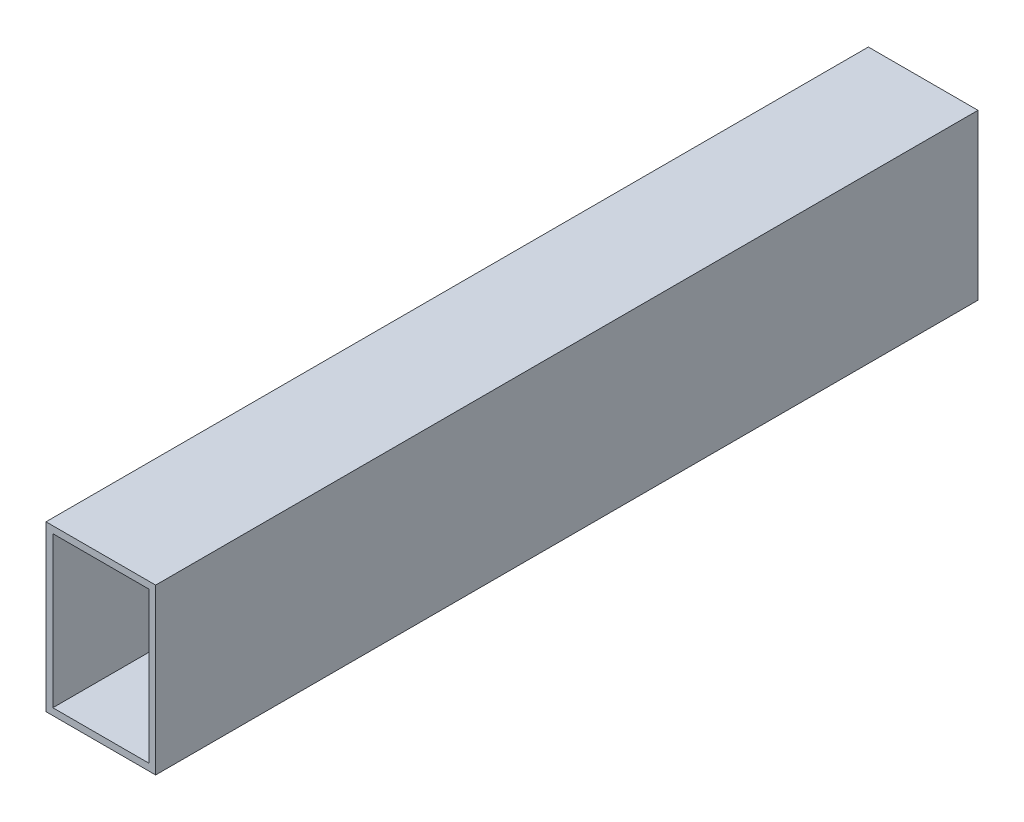
SolidWorks part; units mm, degrees
ref_plane "Front Plane" through (0, 0, 0) normal (0, 0, 1) x (1, 0, 0)
ref_plane "Top Plane" through (0, 0, 0) normal (0, 1, 0) x (1, 0, 0)
ref_plane "Right Plane" through (0, 0, 0) normal (1, 0, 0) x (0, 0, -1)
sketch "Sketch1" plane through (0, 0, 0) normal (0, 0, 1) x (1, 0, 0)
  line L0 (0, 38.1) -> (0, 34.925) construction
  line L1 (-25.4, 38.1) -> (25.4, 38.1)
  line L2 (-25.4, 38.1) -> (-25.4, -38.1)
  line L3 (-25.4, -38.1) -> (25.4, -38.1)
  line L4 (25.4, 38.1) -> (25.4, -38.1)
  line L5 (-25.4, 38.1) -> (25.4, -38.1) construction
  line L6 (-25.4, -38.1) -> (25.4, 38.1) construction
  line L7 (-22.225, 34.925) -> (22.225, 34.925)
  line L8 (-22.225, 34.925) -> (-22.225, -34.925)
  line L9 (-22.225, -34.925) -> (22.225, -34.925)
  line L10 (22.225, 34.925) -> (22.225, -34.925)
  line L11 (22.225, 0) -> (25.4, 0) construction
  line L12 (-22.225, 0) -> (-25.4, 0) construction
  line L13 (0, -34.925) -> (0, -38.1) construction
  point P0 (0, 0)
  dimension "D1" = 76.2
  dimension "D2" = 50.8
  dimension "D3" = 3.175
extrude "Boss-Extrude1" add sketch "Sketch1" along normal blind 381
